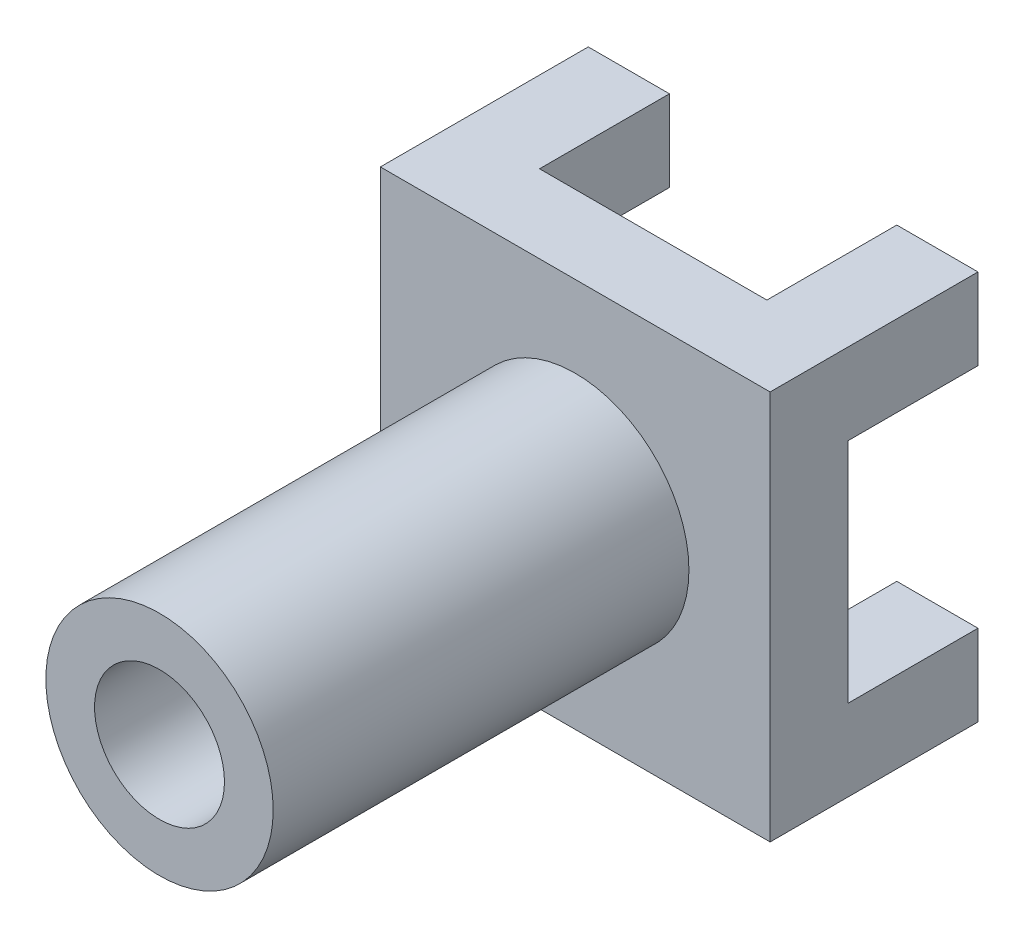
SolidWorks part; units mm, degrees
ref_plane "Alzado" through (0, 0, 0) normal (0, 0, 1) x (1, 0, 0)
ref_plane "Planta" through (0, 0, 0) normal (0, 1, 0) x (1, 0, 0)
ref_plane "Vista lateral" through (0, 0, 0) normal (1, 0, 0) x (0, 0, -1)
sketch "Croquis1" plane through (0, 0, 0) normal (0, 0, 1) x (1, 0, 0)
  line L1 (0, 0) -> (60, 0)
  line L2 (0, 0) -> (0, 60)
  line L3 (0, 60) -> (60, 60)
  line L4 (60, 0) -> (60, 60)
  dimension "D1" = 60
  dimension "D2" = 60
extrude "Saliente-Extruir1" add sketch "Croquis1" against normal blind 12
sketch "Croquis2" plane through (0, 0, 0) normal (0, 0, 1) x (1, 0, 0)
  circle A0 centre (30, 30) radius 17.5
  dimension "D1" = 35
extrude "Saliente-Extruir2" add sketch "Croquis2" along normal blind 64
sketch "Croquis7" plane through (0, 0, 64) normal (0, 0, 1) x (1, 0, 0)
  circle A1 centre (30, 30) radius 10
  dimension "D1" = 20
extrude "Cortar-Extruir1" cut sketch "Croquis7" against normal blind 76
sketch "Croquis8" plane through (0, 0, -12) normal (0, 0, -1) x (-1, 0, 0)
  line L0 (-60, 60) -> (0, 60) construction
  line L1 (-47.5, 47.5) -> (-60, 47.5)
  line L2 (-47.5, 47.5) -> (-47.5, 60)
  line L3 (-47.5, 60) -> (-60, 60)
  line L4 (-60, 47.5) -> (-60, 60)
  point P7 (-30, 60)
  dimension "D1" = 12.5
  dimension "D2" = 12.5
  dimension "D3" = 17.5
extrude "Saliente-Extruir3" add sketch "Croquis8" along normal blind 20
sketch "Croquis9" plane through (0, 0, -32) normal (0, 0, -1) x (-1, 0, 0)
  line L1 (0, 0) -> (-12.5, 0)
  line L2 (0, 0) -> (0, 12.5)
  line L3 (0, 12.5) -> (-12.5, 12.5)
  line L4 (-12.5, 0) -> (-12.5, 12.5)
  dimension "D1" = 12.5
  dimension "D2" = 12.5
sketch "Croquis11" plane through (0, 0, -12) normal (0, 0, -1) x (-1, 0, 0)
  line L1 (-60, 0) -> (-47.5, 0)
  line L2 (-60, 0) -> (-60, 12.5)
  line L3 (-60, 12.5) -> (-47.5, 12.5)
  line L4 (-47.5, 0) -> (-47.5, 12.5)
  dimension "D1" = 12.5
  dimension "D2" = 12.5
extrude "Saliente-Extruir5" add sketch "Croquis11" along normal blind 20
sketch "Croquis12" plane through (0, 0, -12) normal (0, 0, -1) x (-1, 0, 0)
  line L1 (0, 60) -> (-12.5, 60)
  line L2 (0, 60) -> (0, 47.5)
  line L3 (0, 47.5) -> (-12.5, 47.5)
  line L4 (-12.5, 60) -> (-12.5, 47.5)
  dimension "D1" = 12.5
  dimension "D2" = 12.5
extrude "Saliente-Extruir6" add sketch "Croquis12" along normal blind 20
extrude "Saliente-Extruir9" add sketch "Croquis9" against normal blind 20 contours L3 L4 L1 L2
